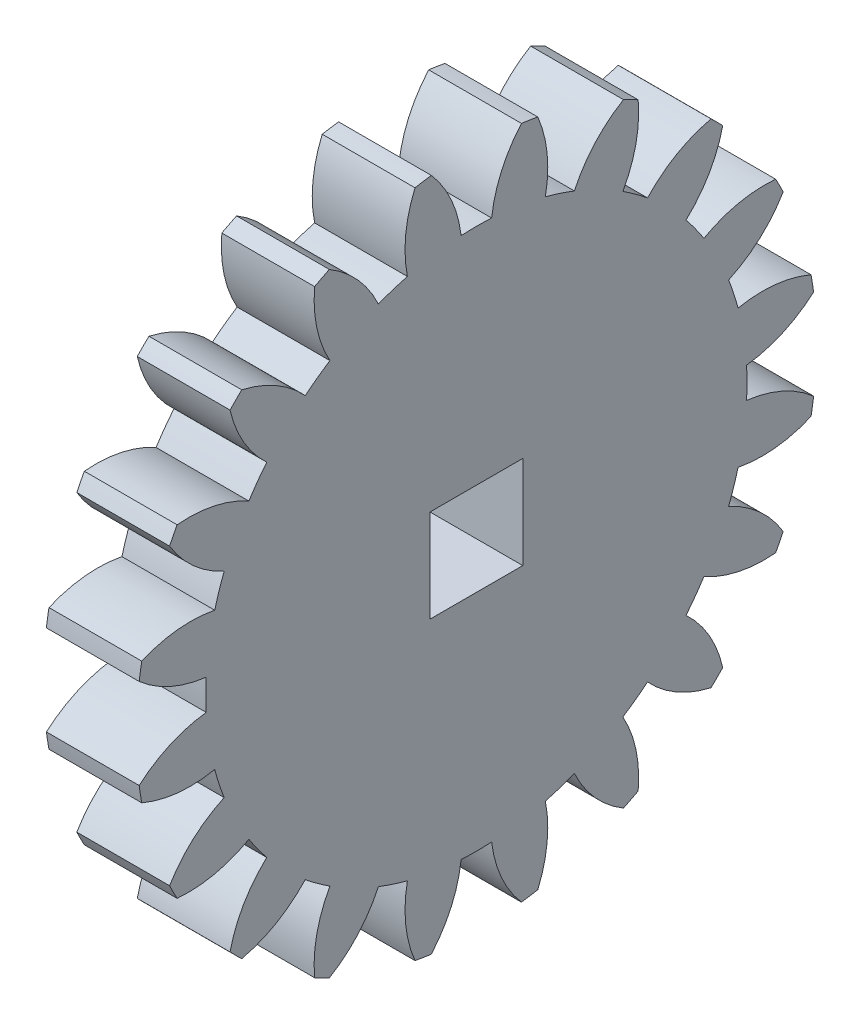
SolidWorks part; units mm, degrees
ref_plane "Plane1" through (0, 0, 0) normal (0, 0, 1) x (1, 0, 0)
ref_plane "Plane2" through (0, 0, 0) normal (0, 1, 0) x (1, 0, 0)
ref_plane "Plane3" through (0, 0, 0) normal (1, 0, 0) x (0, 0, -1)
sketch "HoldingSke" plane through (0, 0, 0) normal (0, 1, 0) x (1, 0, 0)
  line L0 (0, 0) -> (0.4698, -0.171)
  line L1 (-15, 0) -> (100, 0) construction
  line L2 (0, 0) -> (-2.1039, 2.3779)
  line L3 (0, 0) -> (-11.863, 4.5341)
  line L4 (0, 0) -> (8.1152, 2.9537)
  line L5 (0, 0) -> (-46.8476, -17.4728)
  line L6 (0, 0) -> (-4.9738, -3.3558)
  line L7 (-2.1039, 2.3779) -> (8.6586, 51.2059)
  line L8 (-76.2, 54.61) -> (-76.1, 54.61)
  line L9 (-71.009, 38.7566) -> (-53.1078, 45.2721)
  line L10 (-76.2, 71.12) -> (104.1128, 71.12)
  line L11 (0, 0) -> (-6, 0)
  line L12 (-76.2, 101.6) -> (-76.133, 101.6)
  line L13 (24.9733, 27.94) -> (52.9518, 28.4284)
  line L14 (24.9733, 27.94) -> (24.9743, 27.94)
  line L15 (24.9733, 27.94) -> (100.4006, 29.5858)
  line L16 (-63.627, -2) -> (-12.827, -2)
  circle A0 centre (0, 0) radius 0.5
  circle A1 centre (0, 0) radius 17.499
  circle A2 centre (0, 0) radius 37.5
  circle A3 centre (0, 0) radius 0.5
  dimension "MHD" = 34.998
  dimension "Hub_dia" = 75
  dimension "Bore" = 1
  dimension "MBD" = 1
  dimension "Num_teeth" = 20
  dimension "Pitch" = 0.5
  dimension "Overall_len" = 50
  dimension "Show_teeth" = 20
  dimension "Thickness" = 6
  dimension "OAL" = 50.0001
  dimension "T_dim" = 0.1
  dimension "Ap" = 20
  dimension "H" = 19.05
  dimension "Pitch_radius" = 180.3128
  dimension "Width" = 6
  dimension "Backlash" = 0.067
  dimension "Addendum_fac" = 1
  dimension "Dedendum_fac" = 1.25
  dimension "Clearance_fac" = 0.25
  dimension "Dedendum_add" = 0.001
  dimension "Module" = 2
sketch "BasProSke" plane through (0, 0, 0) normal (0, 1, 0) x (1, 0, 0)
  line L0 (-10, 0) -> (60, 0) construction
  line L1 (0, 0) -> (0, 22)
  line L2 (0, 0) -> (6, 0)
  line L3 (6, 0) -> (6, 22)
  line L4 (6, 22) -> (0, 22)
  dimension "Thickness" = 6
  dimension "Diameter" = 44
revolve "Base-Revolve" add sketch "BasProSke" angle 360 about L0
sketch "TooCutSke" plane through (0, 0, 0) normal (1, 0, 0) x (0, 0, -1)
  line L1 (0, 0) -> (0, 107) construction
  line L2 (0, 0) -> (-1.6864, 19.9288) construction
  line L3 (0, 0) -> (-6.2409, 39.4033) construction
  line L4 (-1.6864, 19.9288) -> (-3.1204, 19.7016) construction
  arc A0 (0.9862, 17.4712) -> (-0.9862, 17.4712) centre (0, 0) ccw
  arc A1 (2.9329, 21.8293) -> (-2.9329, 21.8293) centre (0, 0) ccw
  circle A2 centre (0, 0) radius 20 construction
  circle A3 centre (0, 0) radius 18.7939 construction
  arc A4 (-0.9862, 17.4712) -> (-2.9329, 21.8293) centre (-8.9313, 16.536) ccw
  arc A5 (2.9329, 21.8293) -> (0.9862, 17.4712) centre (8.9313, 16.536) ccw
  dimension "Root_dia" = 34.998
  dimension "Overcut_dia" = 44.0508
  dimension "Pitch_dia" = 40
  dimension "Base_dia" = 37.5877
  dimension "Flank_rad" = 8
  dimension "Half_ang" = 9
  dimension "Half_CT" = 1.4519
extrude "ToothCut" cut sketch "TooCutSke" along normal through all
fillet "Breaks" [suppressed] radius 0.04
fillet "RootFillets" [suppressed] radius 0.501
pattern_circular "TeethCuts" count 20 every 18 about axis through (-10, 0, 0) along (1, 0, 0) of "ToothCut", "RootFillets", "Breaks"
sketch "HubNeaOneSke" plane through (0, 0, 0) normal (-1, 0, 0) x (0, 0, 1)
  circle A0 centre (0, 0) radius 17.499
  dimension "Diameter" = 34.998
extrude "HubNearOne" [suppressed] add sketch "HubNeaOneSke" along normal blind 44.0001
sketch "HubNeaBotSke" plane through (0, 0, 0) normal (-1, 0, 0) x (0, 0, 1)
  circle A0 centre (0, 0) radius 17.499
  dimension "Diameter" = 34.998
extrude "HubNearBoth" [suppressed] add sketch "HubNeaBotSke" along normal blind 22
ref_plane "FarPln" through (6, 0, 0) normal (1, 0, 0) x (0, 0, -1)
sketch "HubFarSke" plane through (6, 0, 0) normal (1, 0, 0) x (0, 0, -1)
  circle A0 centre (0, 0) radius 17.499
  dimension "Diameter" = 34.998
extrude "HubFar" [suppressed] add sketch "HubFarSke" along normal blind 22
sketch "BorSke" plane through (0, 0, 0) normal (1, 0, 0) x (0, 0, -1)
  circle A0 centre (0, 0) radius 0.5
  dimension "Diameter" = 1
extrude "Bore" cut sketch "BorSke" along normal mid plane 100.0001
sketch "KeySke" plane through (0, 0, 0) normal (1, 0, 0) x (0, 0, -1)
  line L0 (-0.05, 0) -> (-0.05, 0.6)
  line L1 (-0.05, 0.6) -> (0.05, 0.6)
  line L2 (0.05, 0.6) -> (0.05, 0)
  line L3 (0, 0) -> (0, 34) construction
  line L4 (-0.05, 0) -> (0.05, 0)
  dimension "Offset" = 0.6
  dimension "Width" = 0.1
extrude "Keyway" [suppressed] cut sketch "KeySke" along normal mid plane 100.0001
pattern_circular "Keyway2" [suppressed] count 2 every 90 about axis through (-10, 0, 0) along (1, 0, 0)
sketch "Croquis1" plane through (6, 0, 0) normal (1, 0, 0) x (0, 0, -1)
  line L1 (0, 3) -> (-3, 3)
  line L2 (-3, 3) -> (-3, -3)
  line L3 (-3, -3) -> (3, -3)
  line L4 (3, -3) -> (3, 3)
  line L5 (3, 3) -> (0, 3)
extrude "Cortar-Extruir1" cut sketch "Croquis1" against normal blind 10
equation "' \"Module@HoldingSke\" = 6.35"
equation "' \"Num_teeth@HoldingSke\" = 12"
equation "' \"Ap@HoldingSke\" =  20"
equation "' \"Ap@HoldingSke\" = 20"
equation "' \"Width@HoldingSke\" = 0.5 * 25.4"
equation "' \"Hub_dia@HoldingSke\"= 1 * 25.4"
equation "' \"Hub_dia@HoldingSke\" = 1 * 25.4"
equation "' \"Overall_len@HoldingSke\" = 1.0 * 25.4"
equation "' \"Bore@HoldingSke\" = 0.75 * 25.4"
equation "' \"T_dim@HoldingSke\" = 0.1 * 25.4"
equation "' \"Width@KeySke\" = 0.25 * 25.4"
equation "' \"Show_teeth@HoldingSke\" = 13"
equation "' \"Backlash@HoldingSke\" = 0.009 * 25.4"
equation "' \"Addendum_fac@HoldingSke\" = 1.0"
equation "' \"Dedendum_fac@HoldingSke\" = 1.25"
equation "' \"Dedendum_add@HoldingSke\" = 0.00005 * 25.4"
equation "' \"Clearance_fac@HoldingSke\" = 0.25"
equation "\"Pitch@HoldingSke\" = 1 / \"Module@HoldingSke\""
equation "\"Overcut_dia@TooCutSke\" = (\"Num_teeth@HoldingSke\" + 2 * \"Addendum_fac@HoldingSke\") / \"Pitch@HoldingSke\" + 0.002 * 25.4"
equation "\"Pitch_dia@TooCutSke\" = \"Num_teeth@HoldingSke\" / \"Pitch@HoldingSke\""
equation "\"Base_dia@TooCutSke\" = \"Num_teeth@HoldingSke\" / \"Pitch@HoldingSke\" * cos((\"Ap@HoldingSke\"  * 3.14159265 / 180))"
equation "\"Root_dia@TooCutSke\" = (\"Num_teeth@HoldingSke\" + 2) / \"Pitch@HoldingSke\" - 2 * (\"Addendum_fac@HoldingSke\" + \"Dedendum_fac@HoldingSke\") / \"Pitch@HoldingSke\" - \"Dedendum_add@HoldingSke\" * 2"
equation "\"Half_ang@TooCutSke\" = 180 / \"Num_teeth@HoldingSke\""
equation "\"Half_CT@TooCutSke\" = \"Num_teeth@HoldingSke\" / \"Pitch@HoldingSke\" * sin((3.14159265 / 2 / \"Num_teeth@HoldingSke\")) / 2 - 7 * \"Backlash@HoldingSke\" / 4"
equation "\"Flank_rad@TooCutSke\" = \"Num_teeth@HoldingSke\" / \"Pitch@HoldingSke\" / 5"
equation "\"Radius@RootFillets\" = \"Clearance_fac@HoldingSke\" / \"Pitch@HoldingSke\" + \"Dedendum_add@HoldingSke\""
equation "\"Break_rad@Breaks\" = 0.02 / \"Pitch@HoldingSke\""
equation "\"Thickness@HoldingSke\" = \"Width@HoldingSke\""
equation "\"OAL@HoldingSke\" = \"Thickness@HoldingSke\""
equation "\"MHD@HoldingSke\" = (\"Num_teeth@HoldingSke\" + 2) / \"Pitch@HoldingSke\" - 2 * (\"Addendum_fac@HoldingSke\" + \"Dedendum_fac@HoldingSke\")  / \"Pitch@HoldingSke\" - \"Dedendum_add@HoldingSke\" * 2"
equation "\"MBD@HoldingSke\" = (\"Num_teeth@HoldingSke\" + 2) / \"Pitch@HoldingSke\" - 2 * (\"Addendum_fac@HoldingSke\" + \"Dedendum_fac@HoldingSke\")  / \"Pitch@HoldingSke\" - \"Dedendum_add@HoldingSke\" * 2 - 0.002 * 25.4"
equation "\"MHD@HoldingSke\" = ((sgn( \"MHD@HoldingSke\" - \"Hub_dia@HoldingSke\" )-1)*( \"MHD@HoldingSke\" - \"Hub_dia@HoldingSke\" ))/-2+ \"Hub_dia@HoldingSke\""
equation "\"MBD@HoldingSke\" = ((sgn( \"MBD@HoldingSke\" - \"Bore@HoldingSke\" )-1)*( \"MBD@HoldingSke\" - \"Bore@HoldingSke\" ))/-2+ \"Bore@HoldingSke\""
equation "\"OAL@HoldingSke\" = ((sgn( \"OAL@HoldingSke\" - \"Overall_len@HoldingSke\" )+1)*( \"OAL@HoldingSke\" - \"Overall_len@HoldingSke\" ))/2 + \"Overall_len@HoldingSke\" + 0.000002 * 25.4"
equation "\"Num_teeth@TeethCuts\" = int( \"Show_teeth@HoldingSke\" ) + 1"
equation "\"Num_teeth@TeethCuts\" = ((sgn( \"Num_teeth@TeethCuts\" - \"Num_teeth@HoldingSke\" )-1)*( \"Num_teeth@TeethCuts\" - \"Num_teeth@HoldingSke\" ))/-2+ \"Num_teeth@HoldingSke\""
equation "\"Num_teeth@TeethCuts\" = ((sgn( \"Num_teeth@TeethCuts\" - 2.0)+1)*( \"Num_teeth@TeethCuts\" - 2.0))/2 +2.0"
equation "\"Angle@TeethCuts\" = 360.0 / \"Num_teeth@HoldingSke\""
equation "\"Diameter@BasProSke\" = (\"Num_teeth@HoldingSke\" + 2 * \"Addendum_fac@HoldingSke\") / \"Pitch@HoldingSke\""
equation "\"Thickness@BasProSke\"  = \"Thickness@HoldingSke\""
equation "' \"Fillet_rad@BasProSke\" =  \"Thickness@HoldingSke\" * 0.05"
equation "' \"Fillet_rad@BasProSke\" = \"Thickness@HoldingSke\" * 0.05"
equation "\"MHD@HoldingSke\" = ((sgn( \"MHD@HoldingSke\" - \"Root_dia@TooCutSke\" )-1)*( \"MHD@HoldingSke\" - \"Root_dia@TooCutSke\" ))/-2+ \"Root_dia@TooCutSke\""
equation "\"Diameter@HubNeaOneSke\" = \"MHD@HoldingSke\""
equation "\"Length@HubNearOne\" = \"OAL@HoldingSke\" - \"Thickness@BasProSke\""
equation "\"Diameter@HubNeaBotSke\" = \"MHD@HoldingSke\""
equation "\"Length@HubNearBoth\" = ( \"OAL@HoldingSke\" - \"Thickness@BasProSke\" ) / 2.0"
equation "\"Thickness@FarPln\" = \"Thickness@BasProSke\""
equation "\"Diameter@HubFarSke\" = \"MHD@HoldingSke\""
equation "\"Length@HubFar\" = ( \"OAL@HoldingSke\" - \"Thickness@BasProSke\" ) / 2.0"
equation "\"Diameter@BorSke\" = \"MBD@HoldingSke\""
equation "\"D1@Bore\" = \"OAL@HoldingSke\" * 2.0"
equation "\"D1@Keyway\" = \"OAL@HoldingSke\" * 2.0"
equation "\"Offset@KeySke\" = \"T_dim@HoldingSke\" + \"MBD@HoldingSke\" / 2.0"
